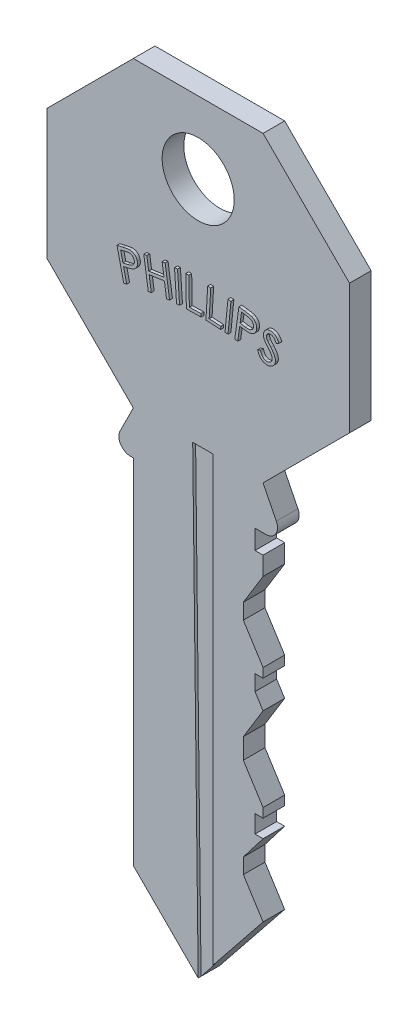
SolidWorks part; units mm, degrees
ref_plane "Alzado" through (0, 0, 0) normal (0, 0, 1) x (1, 0, 0)
ref_plane "Planta" through (0, 0, 0) normal (0, 1, 0) x (1, 0, 0)
ref_plane "Vista lateral" through (0, 0, 0) normal (1, 0, 0) x (0, 0, -1)
sketch "Croquis1" plane through (0, 0, 0) normal (0, 0, 1) x (1, 0, 0)
  line L1 (-10.5, -10.5) -> (10.5, -10.5)
  line L2 (-10.5, -10.5) -> (-10.5, 10.5)
  line L3 (-10.5, 10.5) -> (10.5, 10.5)
  line L4 (10.5, -10.5) -> (10.5, 10.5)
  line L5 (-10.5, -10.5) -> (10.5, 10.5) construction
  line L6 (-10.5, 10.5) -> (10.5, -10.5) construction
  point P0 (0, 0)
  dimension "D1" = 21
  dimension "D2" = 21
extrude "Saliente-Extruir1" add sketch "Croquis1" along normal blind 1.5
sketch "Croquis2" plane through (0, 0, 1.5) normal (0, 0, 1) x (1, 0, 0)
  line L0 (0, 0) -> (-10.5, 0) construction
  line L1 (-10.5, 10.5) -> (-10.5, -10.5) construction
  line L2 (-10.5, 4.5) -> (-4.5, 10.5)
  line L3 (10.5, 10.5) -> (-10.5, 10.5) construction
  line L4 (0, 0) -> (0, 10.5) construction
  line L5 (-10.5, 4.5) -> (-12.9623, 10.5)
  line L6 (-12.9623, 10.5) -> (-10.0297, 11.9891)
  line L7 (-10.0297, 11.9891) -> (-4.5, 10.5)
  line L8 (12.9623, 10.5) -> (10.0297, 11.9891)
  line L9 (10.5, 4.5) -> (12.9623, 10.5)
  line L10 (10.5, 4.5) -> (4.5, 10.5)
  line L11 (10.0297, 11.9891) -> (4.5, 10.5)
  line L12 (10.0297, -11.9891) -> (4.5, -10.5)
  line L13 (10.5, -4.5) -> (4.5, -10.5)
  line L14 (10.5, -4.5) -> (12.9623, -10.5)
  line L15 (12.9623, -10.5) -> (10.0297, -11.9891)
  line L16 (-10.0297, -11.9891) -> (-4.5, -10.5)
  line L17 (-12.9623, -10.5) -> (-10.0297, -11.9891)
  line L18 (-10.5, -4.5) -> (-12.9623, -10.5)
  line L19 (-10.5, -4.5) -> (-4.5, -10.5)
  circle A0 centre (0, 5.5) radius 2.5
  dimension "D3" = 5
  dimension "D4" = 5
  dimension "D1" = 4.5
  dimension "D2" = 4.5
extrude "Cortar-Extruir1" cut sketch "Croquis2" against normal blind 1.5
sketch "Croquis3" plane through (0, 0, 1.5) normal (0, 0, 1) x (1, 0, 0)
  line L0 (-4.5, -10.5) -> (-4.5, -13.5) construction
  line L1 (-4.5, -10.5) -> (-6, -13.5)
  line L2 (-6, -13.5) -> (-4.5, -13.5)
  line L3 (-4.5, -13.5) -> (-4.5, -38)
  line L4 (4.5, -10.5) -> (4.5, -13.5) construction
  line L5 (4.5, -10.5) -> (6, -13.5)
  line L6 (6, -13.5) -> (4.5, -13.5)
  line L7 (4.5, -13.5) -> (4.5, -38)
  line L8 (-4.5, -38) -> (0, -42.5)
  line L9 (0, -42.5) -> (4.5, -38)
  line L10 (-4.5, -10.5) -> (4.5, -10.5)
  dimension "D1" = 3
  dimension "D2" = 1.5
  dimension "D3" = 1.5
  dimension "D4" = 3
  dimension "D5" = 24.5
  dimension "D6" = 24.5
extrude "Saliente-Extruir2" add sketch "Croquis3" against normal blind 1.5
fillet "Redondeo1" radius 0.8 2 edges at (6, -13.5, 0.75) (-6, -13.5, 0.75)
sketch "Croquis4" plane through (0, 0, 1.5) normal (0, 0, 1) x (1, 0, 0)
  line L0 (4.5, -13.5) -> (3.9442, -13.5)
  line L1 (3.9442, -13.5) -> (3.9442, -14.8397)
  line L2 (3.9442, -14.8397) -> (4.5, -14.8397)
  line L3 (4.5, -38) -> (4.5, -13.5) construction
  line L4 (4.5, -14.8397) -> (4.5, -16.1233)
  line L5 (4.5, -16.1233) -> (3.1334, -18.3529)
  line L6 (3.1334, -18.3529) -> (3.1334, -19.4339)
  line L7 (3.1334, -19.4339) -> (4.5, -21.5959)
  line L8 (4.5, -21.5959) -> (4.5, -22.2377)
  line L9 (4.5, -22.2377) -> (3.9442, -22.2377)
  line L10 (3.9442, -22.2377) -> (3.9442, -23.3187)
  line L11 (3.9442, -23.3187) -> (4.5, -24.1981)
  line L12 (4.5, -24.1981) -> (3.1334, -26.4277)
  line L13 (3.1334, -26.4277) -> (3.1334, -27.8461)
  line L14 (3.1334, -27.8461) -> (4.5, -30.0081)
  line L15 (4.5, -30.0081) -> (4.5, -30.6493)
  line L16 (4.5, -30.6493) -> (3.9442, -30.6493)
  line L17 (3.9442, -30.6493) -> (3.9442, -31.8799)
  line L18 (3.9442, -31.8799) -> (4.5, -31.8799)
  line L19 (4.5, -31.8799) -> (3.1334, -33.6596)
  line L20 (3.1334, -33.6596) -> (3.1334, -34.7198)
  line L21 (3.1334, -34.7198) -> (4.5, -36.8818)
  line L22 (4.5, -36.8818) -> (0, -42.5)
  line L23 (0, -42.5) -> (6.6939, -39.2658)
  line L24 (6.6939, -39.2658) -> (9.6019, -27.1369)
  line L25 (9.6019, -27.1369) -> (4.5, -13.5)
extrude "Cortar-Extruir2" cut sketch "Croquis4" against normal blind 1.5
sketch "Croquis5" plane through (0, 0, 1.5) normal (0, 0, 1) x (1, 0, 0)
  line L0 (0, -42.5) -> (-0.3812, -10.5)
  line L1 (-0.3812, -10.5) -> (1.0196, -10.5)
  line L2 (1.0196, -10.5) -> (1.0196, -41.2271)
  line L3 (4.5, -36.8818) -> (0, -42.5) construction
  line L4 (1.0196, -41.2271) -> (0, -42.5)
extrude "Cortar-Extruir3" cut sketch "Croquis5" against normal blind 0.2
sketch "Croquis6" plane through (0, 0, 1.5) normal (0, 0, 1) x (1, 0, 0)
  arc A0 (-5.2108, -3.1955) -> (5.6668, -3.1955) centre (0.228, -23.5736) cw construction
  text T0 "PHILLIPS" font "Century Gothic" height in points 8
extrude "Saliente-Extruir3" add sketch "Croquis6" along normal blind 0.2
